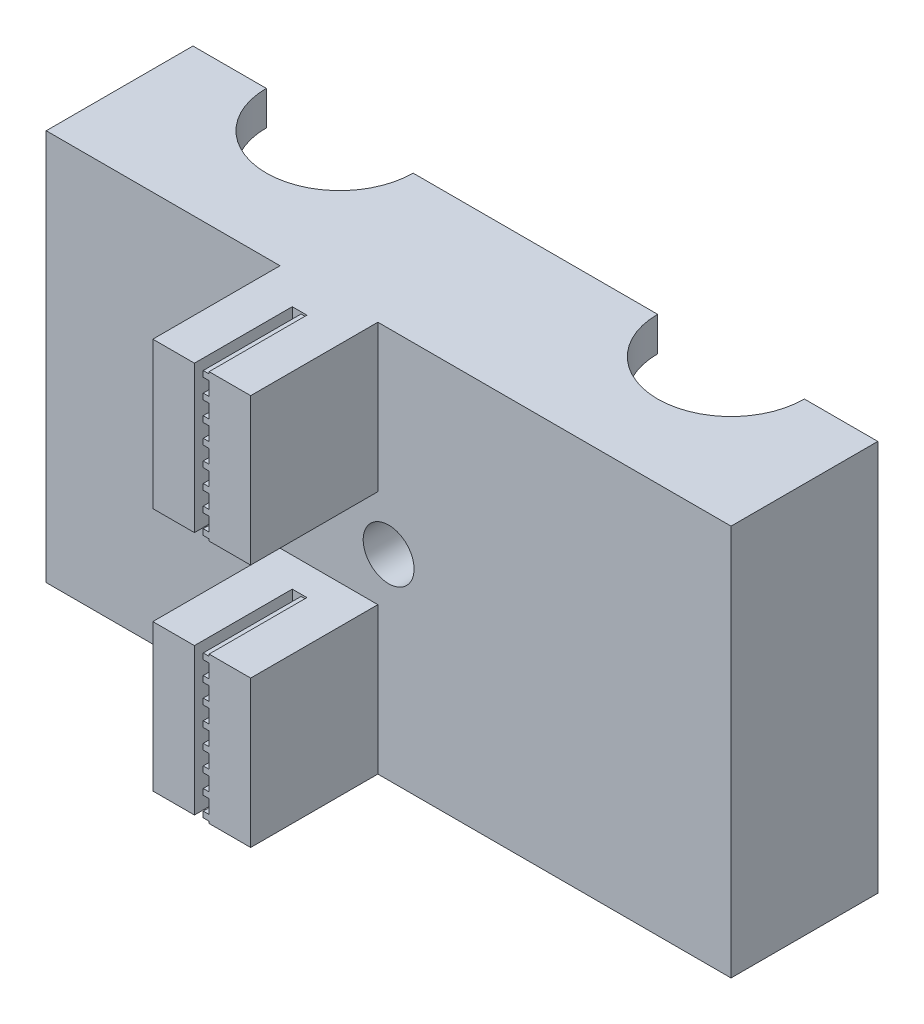
SolidWorks part; units mm, degrees
ref_plane "Front Plane" through (0, 0, 0) normal (0, 0, 1) x (1, 0, 0)
ref_plane "Top Plane" through (0, 0, 0) normal (0, 1, 0) x (1, 0, 0)
ref_plane "Right Plane" through (0, 0, 0) normal (1, 0, 0) x (0, 0, -1)
sketch "Sketch1" plane through (0, 0, 0) normal (0, 0, 1) x (1, 0, 0)
  line L1 (-35, 20) -> (35, 20)
  line L2 (-35, 20) -> (-35, -20)
  line L3 (-35, -20) -> (35, -20)
  line L4 (35, 20) -> (35, -20)
  dimension "D1" = 70
  dimension "D2" = 40
  dimension "D3" = 20
  dimension "D4" = 35
extrude "Boss-Extrude1" add sketch "Sketch1" along normal blind 15
sketch "Sketch2" plane through (0, -20, 0) normal (0, -1, 0) x (1, 0, 0)
  line L0 (-35, 0) -> (35, 0) construction
  line L1 (35, 15) -> (35, 0) construction
  circle A0 centre (-20, 0) radius 7.5
  circle A1 centre (20, 0) radius 7.5
  dimension "D1" = 15
  dimension "D2" = 15
  dimension "D5" = 40
  dimension "D6" = 15
extrude "Cut-Extrude1" cut sketch "Sketch2" against normal through all
sketch "Sketch3" plane through (0, 0, 0) normal (0, 1, 0) x (1, 0, 0)
  circle A0 centre (-20, 0) radius 11.5
  circle A1 centre (20, 0) radius 11.5
  arc A2 (12.5, 0) -> (27.5, 0) centre (20, 0) ccw construction
  arc A3 (-27.5, 0) -> (-12.5, 0) centre (-20, 0) ccw construction
  dimension "D4" = 0
  dimension "D1" = 23
  dimension "D2" = 23
  dimension "D3" = 40
  dimension "D5" = 0
extrude "Cut-Extrude2" cut sketch "Sketch3" against normal mid plane 33
sketch "Sketch4" plane through (0, 0, 15) normal (0, 0, 1) x (1, 0, 0)
  circle A0 centre (0, 0) radius 2.6
  dimension "D1" = 5.2
extrude "Cut-Extrude3" cut sketch "Sketch4" against normal through all
sketch "Sketch5" plane through (0, 0, 15) normal (0, 0, 1) x (1, 0, 0)
  line L2 (35, 20) -> (-35, 20) construction
  line L3 (-1.1, 20) -> (-11.1, 20)
  line L4 (-1.1, 20) -> (-1.1, 5)
  line L6 (-1.1, 5) -> (-11.1, 5)
  line L8 (-11.1, 20) -> (-11.1, 5)
  line L9 (-35, -20) -> (35, -20) construction
  line L10 (-1.1, -20) -> (-11.1, -20)
  line L11 (-1.1, -20) -> (-1.1, -5)
  line L12 (-1.1, -5) -> (-11.1, -5)
  line L13 (-11.1, -20) -> (-11.1, -5)
  dimension "D6" = 15
  dimension "D1" = 10
  dimension "D2" = 1.1
  dimension "D3" = 1.1
  dimension "D4" = 10
  dimension "D5" = 15
extrude "Boss-Extrude2" add sketch "Sketch5" along normal blind 3
sketch "Sketch8" plane through (0, 0, 18) normal (0, 0, 1) x (1, 0, 0)
  line L0 (-11.1, 5) -> (-1.1, 5) construction
  line L1 (-11.1, 20) -> (-6.85, 20)
  line L2 (-11.1, 20) -> (-11.1, 5)
  line L3 (-11.1, 5) -> (-6.85, 5)
  line L4 (-6.85, 20) -> (-6.85, 5)
  line L5 (-11.1, -20) -> (-1.1, -20) construction
  line L6 (-1.1, 20) -> (-5.35, 20)
  line L7 (-1.1, 20) -> (-1.1, 5)
  line L8 (-1.1, 5) -> (-5.35, 5)
  line L9 (-5.35, 20) -> (-5.35, 5)
  line L10 (-11.1, -5) -> (-6.85, -5)
  line L11 (-11.1, -5) -> (-11.1, -20)
  line L12 (-11.1, -20) -> (-6.85, -20)
  line L13 (-6.85, -5) -> (-6.85, -20)
  line L15 (-1.1, -5) -> (-5.35, -5)
  line L16 (-1.1, -5) -> (-1.1, -20)
  line L17 (-1.1, -20) -> (-5.35, -20)
  line L18 (-5.35, -5) -> (-5.35, -20)
  dimension "D1" = 4.25
  dimension "D2" = 4.25
  dimension "D3" = 4.25
  dimension "D4" = 4.25
extrude "Boss-Extrude5" add sketch "Sketch8" along normal blind 10
sketch "Sketch9" plane through (0, 0, 18) normal (0, 0, 1) x (1, 0, 0)
  line L0 (-5.35, 20) -> (-5.35, 5) construction
  line L1 (-5.35, 19.8) -> (-5.95, 19.8)
  line L2 (-5.35, 19.8) -> (-5.35, 19.2)
  line L3 (-5.35, 19.2) -> (-5.95, 19.2)
  line L4 (-5.95, 19.8) -> (-5.95, 19.2)
  line L5 (-5.35, 20) -> (-6.85, 20) construction
  line L6 (-5.35, 17.8) -> (-5.95, 17.8)
  line L7 (-5.35, 17.8) -> (-5.35, 17.2)
  line L8 (-5.35, 17.2) -> (-5.95, 17.2)
  line L9 (-5.95, 17.8) -> (-5.95, 17.2)
  line L10 (-5.35, 15.8) -> (-5.95, 15.8)
  line L11 (-5.35, 15.8) -> (-5.35, 15.2)
  line L12 (-5.35, 15.2) -> (-5.95, 15.2)
  line L13 (-5.95, 15.8) -> (-5.95, 15.2)
  line L14 (-5.35, 13.8) -> (-5.95, 13.8)
  line L15 (-5.35, 13.8) -> (-5.35, 13.2)
  line L16 (-5.35, 13.2) -> (-5.95, 13.2)
  line L17 (-5.95, 13.8) -> (-5.95, 13.2)
  line L18 (-5.35, 11.8) -> (-5.95, 11.8)
  line L19 (-5.35, 11.8) -> (-5.35, 11.2)
  line L20 (-5.35, 11.2) -> (-5.95, 11.2)
  line L21 (-5.95, 11.8) -> (-5.95, 11.2)
  line L22 (-5.35, 9.8) -> (-5.95, 9.8)
  line L23 (-5.35, 9.8) -> (-5.35, 9.2)
  line L24 (-5.35, 9.2) -> (-5.95, 9.2)
  line L25 (-5.95, 9.8) -> (-5.95, 9.2)
  line L26 (-5.35, 7.8) -> (-5.95, 7.8)
  line L27 (-5.35, 7.8) -> (-5.35, 7.2)
  line L28 (-5.35, 7.2) -> (-5.95, 7.2)
  line L29 (-5.95, 7.8) -> (-5.95, 7.2)
  line L30 (-5.35, 5.8) -> (-5.95, 5.8)
  line L31 (-5.35, 5.8) -> (-5.35, 5.2)
  line L32 (-5.35, 5.2) -> (-5.95, 5.2)
  line L33 (-5.95, 5.8) -> (-5.95, 5.2)
  line L34 (-5.35, -5) -> (-5.35, -20) construction
  line L35 (-5.35, -19.8) -> (-5.95, -19.8)
  line L36 (-5.35, -19.8) -> (-5.35, -19.2)
  line L37 (-5.35, -19.2) -> (-5.95, -19.2)
  line L38 (-5.95, -19.8) -> (-5.95, -19.2)
  line L39 (-6.85, -20) -> (-5.35, -20) construction
  line L40 (-5.35, -17.8) -> (-5.95, -17.8)
  line L41 (-5.35, -17.8) -> (-5.35, -17.2)
  line L42 (-5.35, -17.2) -> (-5.95, -17.2)
  line L43 (-5.95, -17.8) -> (-5.95, -17.2)
  line L44 (-5.35, -15.8) -> (-5.95, -15.8)
  line L45 (-5.35, -15.8) -> (-5.35, -15.2)
  line L46 (-5.35, -15.2) -> (-5.95, -15.2)
  line L47 (-5.95, -15.8) -> (-5.95, -15.2)
  line L48 (-5.35, -13.8) -> (-5.95, -13.8)
  line L49 (-5.35, -13.8) -> (-5.35, -13.2)
  line L50 (-5.35, -13.2) -> (-5.95, -13.2)
  line L51 (-5.95, -13.8) -> (-5.95, -13.2)
  line L52 (-5.35, -11.8) -> (-5.95, -11.8)
  line L53 (-5.35, -11.8) -> (-5.35, -11.2)
  line L54 (-5.35, -11.2) -> (-5.95, -11.2)
  line L55 (-5.95, -11.8) -> (-5.95, -11.2)
  line L56 (-5.35, -9.8) -> (-5.95, -9.8)
  line L57 (-5.35, -9.8) -> (-5.35, -9.2)
  line L58 (-5.35, -9.2) -> (-5.95, -9.2)
  line L59 (-5.95, -9.8) -> (-5.95, -9.2)
  line L60 (-5.35, -7.8) -> (-5.95, -7.8)
  line L61 (-5.35, -7.8) -> (-5.35, -7.2)
  line L62 (-5.35, -7.2) -> (-5.95, -7.2)
  line L63 (-5.95, -7.8) -> (-5.95, -7.2)
  line L64 (-5.35, -5.8) -> (-5.95, -5.8)
  line L65 (-5.35, -5.8) -> (-5.35, -5.2)
  line L66 (-5.35, -5.2) -> (-5.95, -5.2)
  line L67 (-5.95, -5.8) -> (-5.95, -5.2)
  dimension "D1" = 0.6
  dimension "D2" = 0.6
  dimension "D3" = 0.2
  dimension "D5" = 0.6
  dimension "D6" = 0.6
  dimension "D7" = 0.2
  dimension "D4" = 8
  dimension "D8" = 8
extrude "Boss-Extrude6" add sketch "Sketch9" along normal blind 10
equation "\"D3@Sketch1\"=\"D2@Sketch1\"/2"
equation "\"D4@Sketch1\"=\"D1@Sketch1\"/2"
equation "\"D2@Sketch2\"=\"D1@Sketch2\""
equation "\"D2@Sketch3\"=\"D1@Sketch3\""
equation "\"D4@Sketch5\"=\"D1@Sketch5\""
equation "\"D3@Sketch5\"=\"D2@Sketch5\""
equation "\"D6@Sketch5\"=\"D5@Sketch5\""
equation "\"D2@Sketch8\"=\"D1@Sketch8\""
equation "\"D3@Sketch8\"=\"D1@Sketch8\""
equation "\"D4@Sketch8\"=\"D1@Sketch8\""
